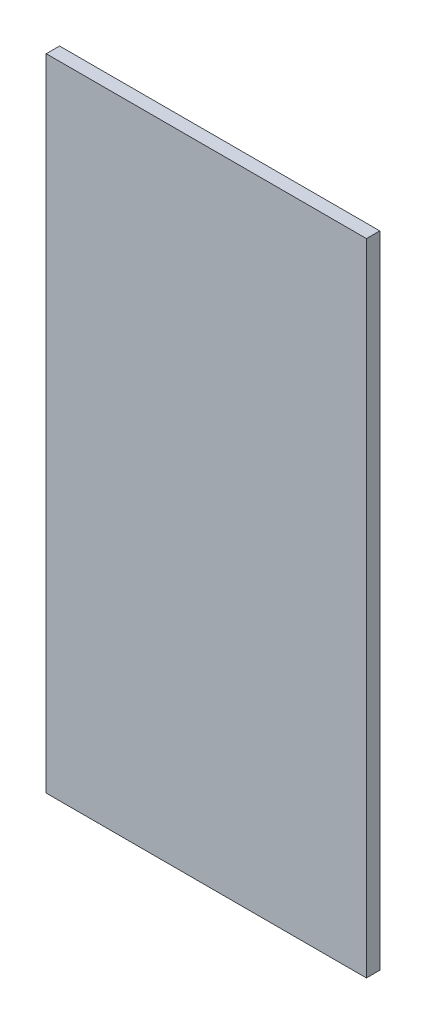
SolidWorks part; units mm, degrees
ref_plane "Front Plane" through (0, 0, 0) normal (0, 0, 1) x (1, 0, 0)
ref_plane "Top Plane" through (0, 0, 0) normal (0, 1, 0) x (1, 0, 0)
ref_plane "Right Plane" through (0, 0, 0) normal (1, 0, 0) x (0, 0, -1)
sketch "Sketch2" plane through (0, 0, 0) normal (0, 0, 1) x (1, 0, 0)
  line L3 (-152.4, 304.8) -> (152.4, 304.8)
  line L4 (-152.4, 304.8) -> (-152.4, -304.8)
  line L5 (-152.4, -304.8) -> (152.4, -304.8)
  line L6 (152.4, 304.8) -> (152.4, -304.8)
  dimension "D1" = 152.4
  dimension "D2" = 609.6
  dimension "D3" = 304.8
  dimension "D4" = 304.8
extrude "Boss-Extrude1" add sketch "Sketch2" along normal mid plane 12.7 contours L4 L5 L6 L3
